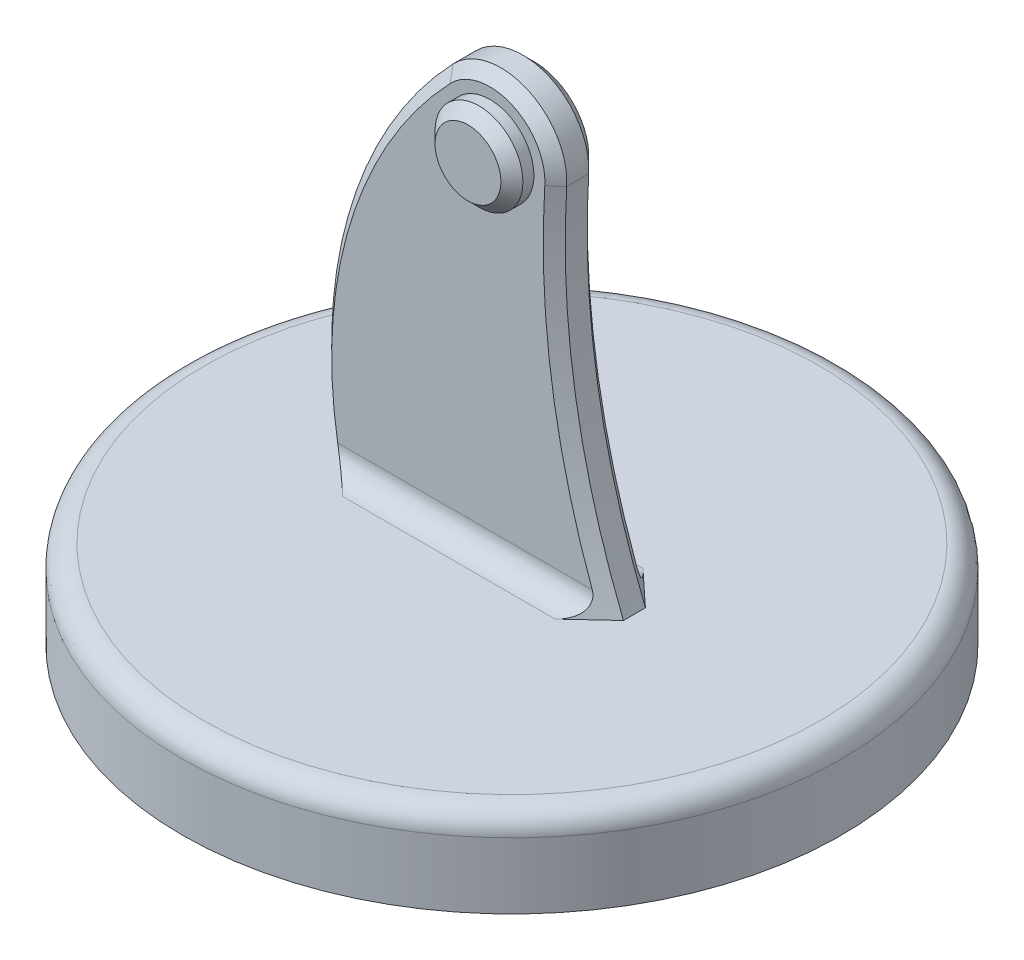
SolidWorks part; units mm, degrees
material "可锻铸铁"
ref_plane "前视基准面" through (0, 0, 0) normal (0, 0, 1) x (1, 0, 0)
ref_plane "上视基准面" through (0, 0, 0) normal (0, 1, 0) x (1, 0, 0)
ref_plane "右视基准面" through (0, 0, 0) normal (1, 0, 0) x (0, 0, -1)
sketch "草图1" plane through (0, 0, 0) normal (0, 1, 0) x (1, 0, 0)
  circle A0 centre (0, 0) radius 75
  dimension "D1" = 150
extrude "凸台-拉伸1" add sketch "草图1" along normal blind 20
fillet "圆角2" radius 5 1 edges at (0, 20, 75)
sketch "草图4" plane through (0, 0, 0) normal (0, 0, 1) x (1, 0, 0)
  line L0 (0, 0) -> (0, 100) construction
  line L3 (-75, 15) -> (75, 15) construction
  line L4 (30, 15) -> (-35, 15)
  arc A0 (14.9706, 99.062) -> (-10.8492, 110.3583) centre (0, 100) ccw
  arc A1 (-35, 15) -> (-10.8492, 110.3583) centre (61.4788, 41.3028) cw
  arc A2 (14.9706, 99.062) -> (30, 15) centre (194.6184, 87.8065) ccw
  dimension "D4" = 30
  dimension "D5" = 100
  dimension "D6" = 180
  dimension "D1" = 30
  dimension "D2" = 35
  dimension "D3" = 100
extrude "凸台-拉伸2" add sketch "草图4" along normal mid plane 10
chamfer "倒角1" distance 2.5 angle 45 6 edges at (-34.7965, 68.3412, -5) (16.9703, 58.8038, -5) (6.0123, 113.7423, -5) (16.9703, 58.8038, 5) (-34.7965, 68.3412, 5) (6.0123, 113.7423, 5)
fillet "圆角3" radius 5 2 edges at (-4.2415, 20, -5) (-4.2415, 20, 5)
sketch "草图5" plane through (0, 0, 5) normal (0, 0, 1) x (1, 0, 0)
  circle A0 centre (0, 100) radius 10
  dimension "D1" = 20
extrude "凸台-拉伸3" add sketch "草图5" along normal blind 5
chamfer "倒角2" distance 2.5 angle 45 1 edges at (10, 100, 10)
sketch "草图6" plane through (0, 0, -5) normal (0, 0, -1) x (-1, 0, 0)
  circle A0 centre (0, 100) radius 5
  dimension "D1" = 10
extrude "切除-拉伸1" cut sketch "草图6" against normal blind 10
